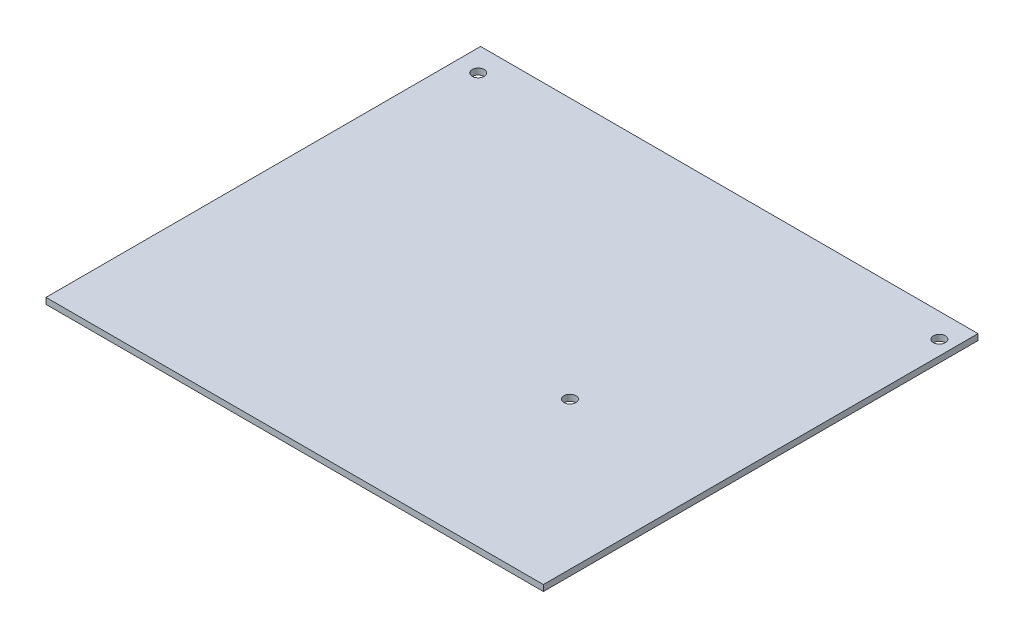
SolidWorks part; units mm, degrees
ref_plane "Front Plane" through (0, 0, 0) normal (0, 0, 1) x (1, 0, 0)
ref_plane "Top Plane" through (0, 0, 0) normal (0, 1, 0) x (1, 0, 0)
ref_plane "Right Plane" through (0, 0, 0) normal (1, 0, 0) x (0, 0, -1)
sketch "Sketch1" plane through (0, 0, 0) normal (0, 1, 0) x (1, 0, 0)
  line L0 (0, 0) -> (0, 28916.8791) construction
  line L1 (-65.405, -57.15) -> (65.405, -57.15)
  line L2 (-65.405, -57.15) -> (-65.405, 57.15)
  line L3 (-65.405, 57.15) -> (65.405, 57.15)
  line L4 (65.405, -57.15) -> (65.405, 57.15)
  line L5 (-65.405, -57.15) -> (65.405, 57.15) construction
  line L6 (-65.405, 57.15) -> (65.405, -57.15) construction
  line L7 (0, 0) -> (28916.8791, 0) construction
  circle A0 centre (61.595, 50.8) radius 1.5748
  circle A3 centre (-59.69, 50.8) radius 1.5748
  circle A4 centre (26.67, -11.43) radius 1.5748
  point P0 (0, 0)
  point P14 (0, 0)
  dimension "D7" = 3.1496
  dimension "D1" = 92.075
  dimension "D2" = 45.72
  dimension "D3" = 130.81
  dimension "D4" = 114.3
  dimension "D5" = 127
  dimension "D6" = 107.95
  dimension "D8" = 5.715
extrude "Boss-Extrude1" add sketch "Sketch1" along normal blind 1.6
